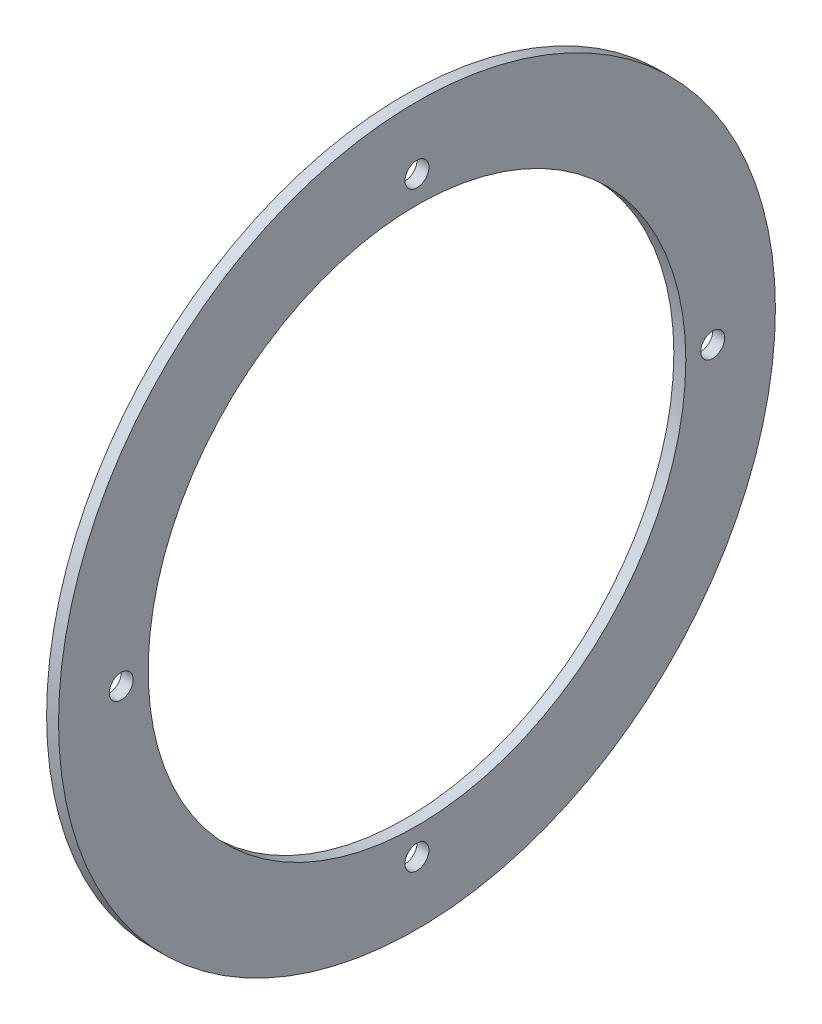
SolidWorks part; units mm, degrees
material "普通碳钢"
ref_plane "前视" through (0, 0, 0) normal (0, 0, 1) x (1, 0, 0)
ref_plane "上视" through (0, 0, 0) normal (0, 1, 0) x (1, 0, 0)
ref_plane "右视" through (0, 0, 0) normal (1, 0, 0) x (0, 0, -1)
sketch "草图1" plane through (0, 0, 0) normal (1, 0, 0) x (0, 0, -1)
  circle A0 centre (0, 0) radius 45
  circle A1 centre (0, 0) radius 60
  circle A2 centre (0, 0) radius 49.5 construction
  circle A3 centre (0, 49.5) radius 2
  circle A4 centre (-49.5, 0) radius 2
  circle A5 centre (0, -49.5) radius 2
  circle A6 centre (49.5, 0) radius 2
  dimension "D1" = 120
  dimension "D2" = 90
  dimension "D3" = 99
  dimension "D4" = 4
extrude "凸台-拉伸1" add sketch "草图1" along normal blind 2
